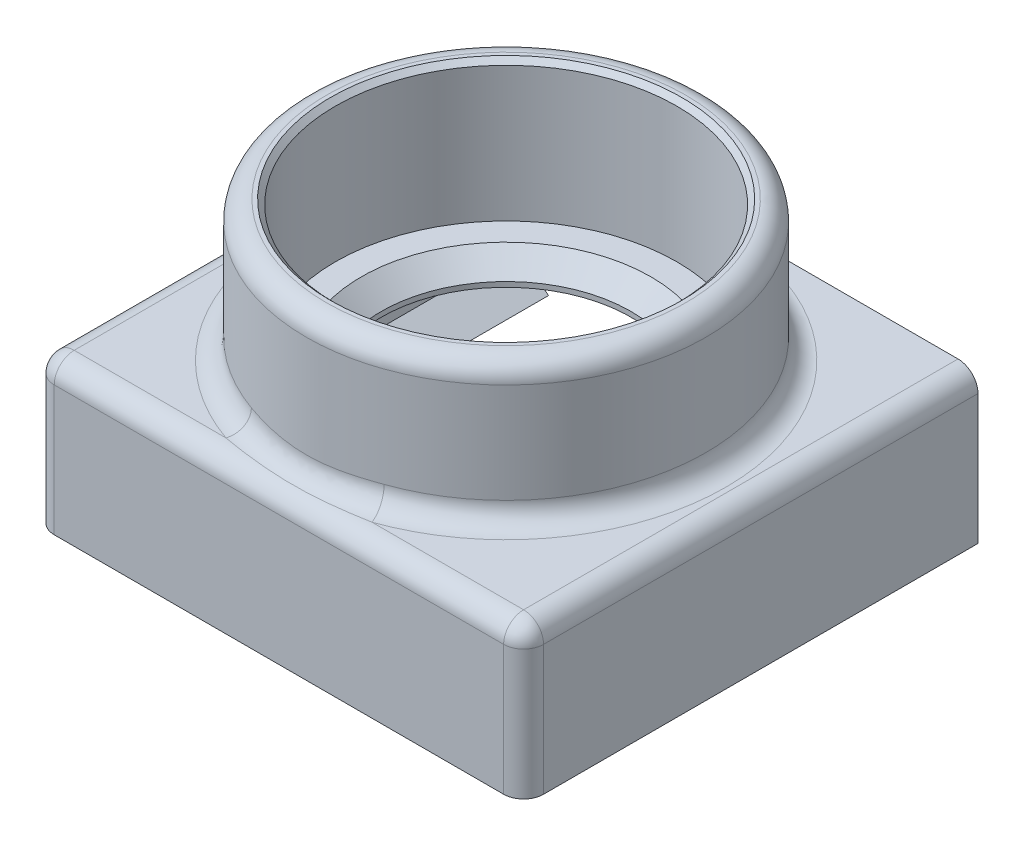
SolidWorks part; units mm, degrees
ref_plane "Plan de face" through (0, 0, 0) normal (0, 0, 1) x (1, 0, 0)
ref_plane "Plan de dessus" through (0, 0, 0) normal (0, 1, 0) x (1, 0, 0)
ref_plane "Plan de droite" through (0, 0, 0) normal (1, 0, 0) x (0, 0, -1)
sketch "Esquisse1" plane through (0, 0, 0) normal (0, 0, 1) x (1, 0, 0)
  line L0 (6, 0) -> (0, 0)
  line L1 (0, 0) -> (0, 15)
  line L2 (0, 15) -> (49, 15)
  line L3 (49, 15) -> (49, 0)
  line L4 (49, 0) -> (43, 0)
  line L5 (43, 0) -> (47, 3)
  line L11 (6, 0) -> (2, 3)
  line L15 (2, 12.5) -> (2, 3)
  line L16 (47, 3) -> (47, 12.5)
  line L17 (47, 12.5) -> (2, 12.5)
  dimension "D1" = 49
  dimension "D4" = 6
  dimension "D5" = 3
  dimension "D7" = 15
  dimension "D10" = 3
  dimension "D11" = 6
extrude "Boss.-Extru.1" add sketch "Esquisse1" along normal blind 43.5
sketch "Esquisse2" plane through (0, 0, 0) normal (-1, 0, 0) x (0, 0, 1)
  line L1 (43.5, 0) -> (45.5, 0)
  line L2 (43.5, 0) -> (43.5, 15)
  line L3 (43.5, 15) -> (45.5, 15)
  line L4 (45.5, 0) -> (45.5, 15)
  dimension "D1" = 15
  dimension "D2" = 2
extrude "Boss.-Extru.2" add sketch "Esquisse2" against normal blind 49
sketch "Esquisse4" plane through (0, 0, 43.5) normal (0, 0, -1) x (-1, 0, 0)
  line L1 (-47, 12.5) -> (-45, 12.5)
  line L2 (-47, 12.5) -> (-47, 3.6)
  line L3 (-47, 3.6) -> (-45, 3.6)
  line L4 (-45, 12.5) -> (-45, 3.6)
  line L5 (-2, 12.5) -> (-4, 12.5)
  line L6 (-2, 12.5) -> (-2, 3.6)
  line L7 (-2, 3.6) -> (-4, 3.6)
  line L8 (-4, 12.5) -> (-4, 3.6)
  dimension "D1" = 0.6
  dimension "D2" = 2
  dimension "D3" = 0.6
  dimension "D4" = 2
extrude "Boss.-Extru.3" add sketch "Esquisse4" along normal blind 39
sketch "Esquisse5" plane through (0, 0, 4.5) normal (0, 0, -1) x (-1, 0, 0)
  line L1 (-47, 12.5) -> (-42, 12.5)
  line L2 (-47, 12.5) -> (-47, 7.5)
  line L3 (-47, 7.5) -> (-42, 7.5)
  line L4 (-42, 12.5) -> (-42, 7.5)
  line L5 (-2, 12.5) -> (-7, 12.5)
  line L6 (-2, 12.5) -> (-2, 7.5)
  line L7 (-2, 7.5) -> (-7, 7.5)
  line L8 (-7, 12.5) -> (-7, 7.5)
  dimension "D1" = 5
  dimension "D2" = 5
  dimension "D3" = 5
  dimension "D4" = 5
extrude "Boss.-Extru.4" add sketch "Esquisse5" along normal blind 4.5
fillet "Congé1" radius 2 2 edges at (45, 12.5, 24) (4, 12.5, 24)
fillet "Congé2" radius 2 2 edges at (7, 12.5, 2.25) (42, 12.5, 2.25)
fillet "Congé5" radius 2 5 edges at (0, 7.5, 45.5) (49, 7.5, 45.5) (24.5, 15, 45.5) (0, 15, 22.75) (49, 15, 22.75)
sketch "Esquisse6" plane through (0, 15, 0) normal (0, 1, 0) x (1, 0, 0)
  circle A0 centre (24.5, -22.75) radius 12.5
  dimension "D1" = 25
extrude "Enlèv. mat.-Extru.1" cut sketch "Esquisse6" against normal blind 2.5
chamfer "Chanfrein1" distance 2 angle 45 1 edges at (24.5, 15, 35.25)
sketch "Esquisse7" plane through (0, 0, 0) normal (0, 0, -1) x (-1, 0, 0)
  line L0 (-47, 7.5) -> (-42, 7.5) construction
  line L1 (-49, 0) -> (-49, 13) construction
  line L2 (-7, 7.5) -> (-2, 7.5) construction
  line L3 (0, 13) -> (0, 0) construction
  line L4 (-47, 15) -> (-2, 15) construction
  circle A0 centre (-45.5, 11) radius 1.8
  circle A1 centre (-3.5, 11) radius 1.8
  dimension "D1" = 3.6
  dimension "D2" = 3.6
  dimension "D3" = 3.5
  dimension "D4" = 3.5
  dimension "D5" = 3.5
  dimension "D6" = 3.5
  dimension "D7" = 4
extrude "Enlèv. mat.-Extru.2" cut sketch "Esquisse7" against normal blind 3.8
chamfer "Chanfrein3" distance 0.5 angle 45 2 edges at (1.7, 11, 0) (43.7, 11, 0)
sketch "Esquisse8" plane through (0, 15, 0) normal (0, 1, 0) x (1, 0, 0)
  circle A0 centre (24.5, -22.75) radius 17.1
  circle A1 centre (24.5, -22.75) radius 20
  dimension "D1" = 34.2
  dimension "D2" = 40
extrude "Boss.-Extru.5" add sketch "Esquisse8" along normal blind 14 contours A1 A0
fillet "Congé6" radius 2 1 edges at (24.5, 15, 2.75)
fillet "Congé7" radius 2 1 edges at (24.5, 29, 42.75)
chamfer "Chanfrein4" distance 0.5 angle 45 1 edges at (24.5, 29, 39.85)
